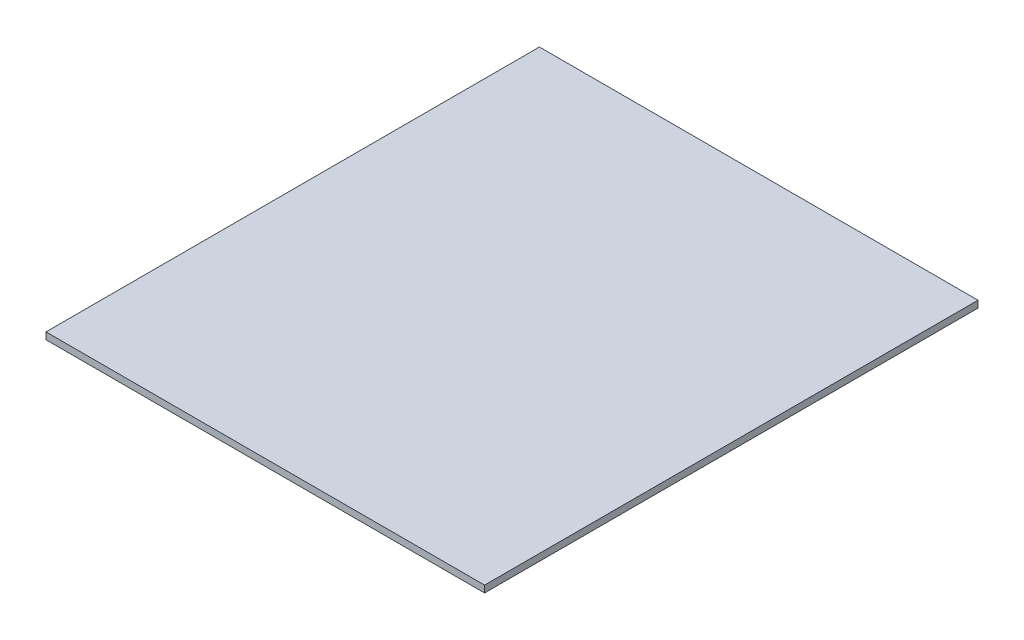
SolidWorks part; units mm, degrees
material "6061-T6 (SS)"
ref_plane "Front Plane" through (0, 0, 0) normal (0, 0, 1) x (1, 0, 0)
ref_plane "Top Plane" through (0, 0, 0) normal (0, 1, 0) x (1, 0, 0)
ref_plane "Right Plane" through (0, 0, 0) normal (1, 0, 0) x (0, 0, -1)
sketch "Sketch2" plane through (0, 0, 0) normal (0, 1, 0) x (1, 0, 0)
  line L1 (-203.2, -228.6) -> (203.2, -228.6)
  line L2 (-203.2, -228.6) -> (-203.2, 228.6)
  line L3 (-203.2, 228.6) -> (203.2, 228.6)
  line L4 (203.2, -228.6) -> (203.2, 228.6)
  line L5 (-203.2, -228.6) -> (203.2, 228.6) construction
  line L6 (-203.2, 228.6) -> (203.2, -228.6) construction
  point P0 (0, 0)
  dimension "D1" = 457.2
  dimension "D2" = 406.4
extrude "Boss-Extrude1" add sketch "Sketch2" along normal blind 6.35
